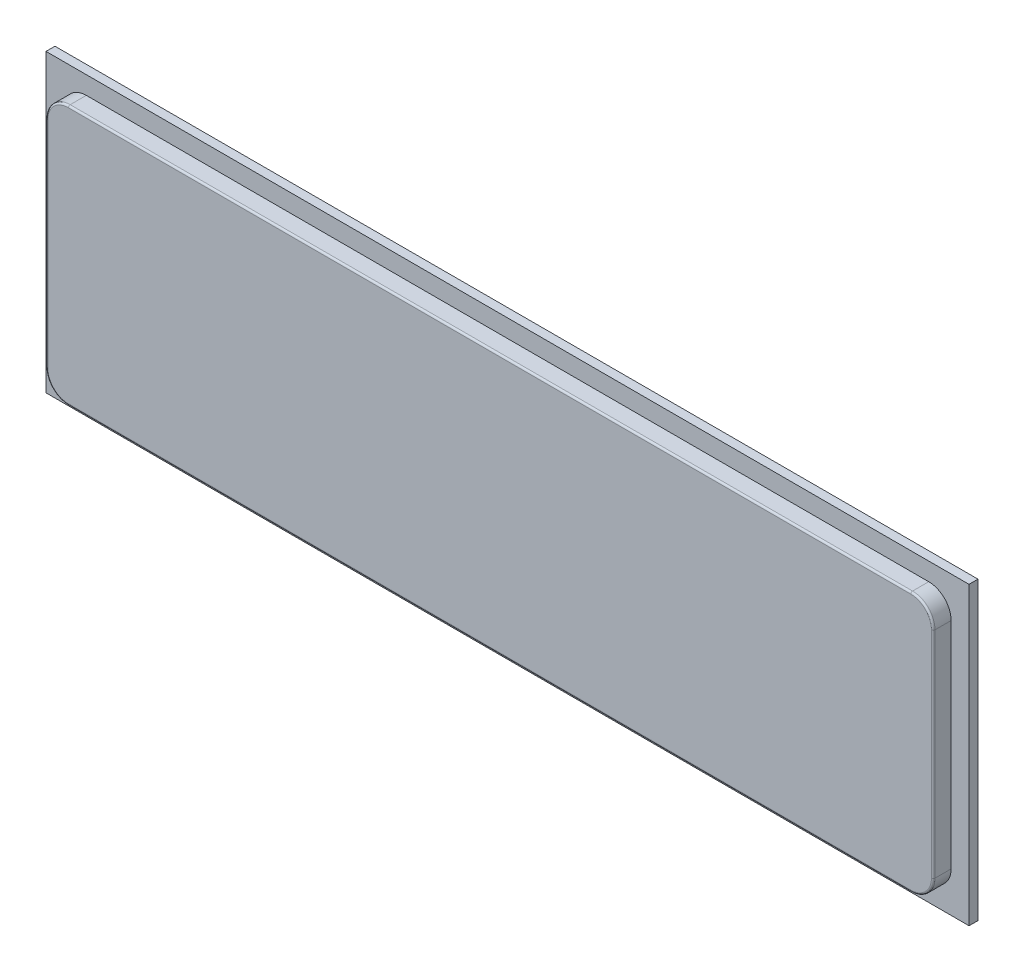
SolidWorks part; units mm, degrees
ref_plane "Спереди" through (0, 0, 0) normal (0, 0, 1) x (1, 0, 0)
ref_plane "Сверху" through (0, 0, 0) normal (0, 1, 0) x (1, 0, 0)
ref_plane "Справа" through (0, 0, 0) normal (1, 0, 0) x (0, 0, -1)
sketch "Эскиз1" plane through (0, 0, 0) normal (0, 0, 1) x (1, 0, 0)
  line L0 (-120, 25) -> (-120, -5) construction
  line L1 (-120, 25) -> (-20, 25) construction
  line L2 (-120, -5) -> (-20, -5) construction
  line L3 (-20, 25) -> (-20, -5) construction
  line L4 (-120, 25) -> (-120, -5)
  line L5 (-120, 25) -> (-20, 25)
  line L6 (-120, -5) -> (-20, -5)
  line L7 (-20, 25) -> (-20, -5)
  line L8 (-119.5, 24.5) -> (-119.5, -4.5)
  line L9 (-119.5, -4.5) -> (-20.5, -4.5)
  line L10 (-20.5, 24.5) -> (-20.5, -4.5)
  line L11 (-119.5, 24.5) -> (-20.5, 24.5)
  dimension "D1" = 0.5
extrude "Бобышка-Вытянуть2" add sketch "Эскиз1" against normal blind 2 contours L11 L10 L9 L8
fillet "Скругление1" radius 2.5 4 edges at (-20.5, -4.5, -1) (-119.5, -4.5, -1) (-119.5, 24.5, -1) (-20.5, 24.5, -1)
sketch "Эскиз3" plane through (0, 0, -2) normal (0, 0, 1) x (1, 0, 0)
  line L0 (-117, 24.5) -> (-23, 24.5) construction
  line L1 (-121.5, 26.5) -> (-18.5, 26.5)
  line L2 (-121.5, 26.5) -> (-121.5, -6.5)
  line L3 (-121.5, -6.5) -> (-18.5, -6.5)
  line L4 (-18.5, 26.5) -> (-18.5, -6.5)
  line L5 (-119.5, 22) -> (-119.5, -2) construction
  line L6 (-20.5, 22) -> (-20.5, -2) construction
  line L7 (-117, -4.5) -> (-23, -4.5) construction
  dimension "D1" = 2
  dimension "D2" = 2
  dimension "D3" = 2
  dimension "D4" = 2
extrude "Бобышка-Вытянуть3" add sketch "Эскиз3" against normal blind 1
fillet "Скругление2" radius 0.2 8 edges at (-118.7678, -3.7678, 0) (-119.5, 10, 0) (-118.7678, 23.7678, 0) (-70, 24.5, 0) (-21.2322, 23.7678, 0) (-20.5, 10, 0) (-21.2322, -3.7678, 0) (-70, -4.5, 0)
